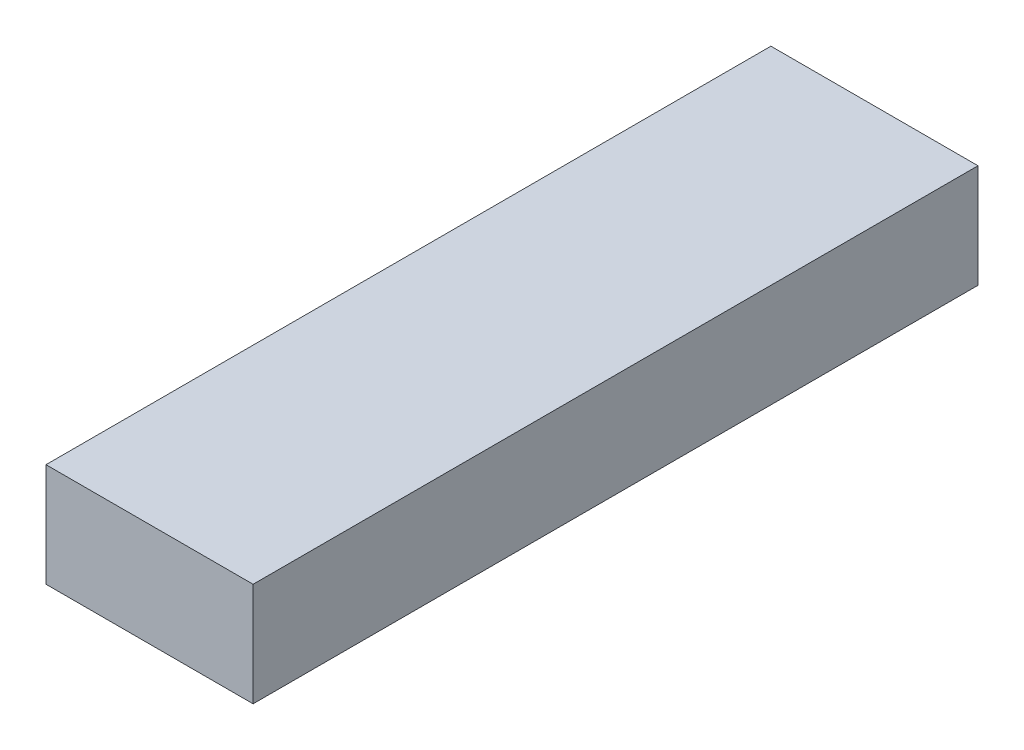
SolidWorks part; units mm, degrees
ref_plane "Front Plane" through (0, 0, 0) normal (0, 0, 1) x (1, 0, 0)
ref_plane "Top Plane" through (0, 0, 0) normal (0, 1, 0) x (1, 0, 0)
ref_plane "Right Plane" through (0, 0, 0) normal (1, 0, 0) x (0, 0, -1)
sketch "Sketch1" plane through (0, 0, 0) normal (0, 0, 1) x (1, 0, 0)
  line L1 (-25.4, -12.7) -> (25.4, -12.7)
  line L2 (-25.4, -12.7) -> (-25.4, 12.7)
  line L3 (-25.4, 12.7) -> (25.4, 12.7)
  line L4 (25.4, -12.7) -> (25.4, 12.7)
  line L5 (-25.4, -12.7) -> (25.4, 12.7) construction
  line L6 (-25.4, 12.7) -> (25.4, -12.7) construction
  point P0 (0, 0)
  dimension "D1" = 25.4
  dimension "D2" = 50.8
extrude "Boss-Extrude1" add sketch "Sketch1" along normal blind 177.8
